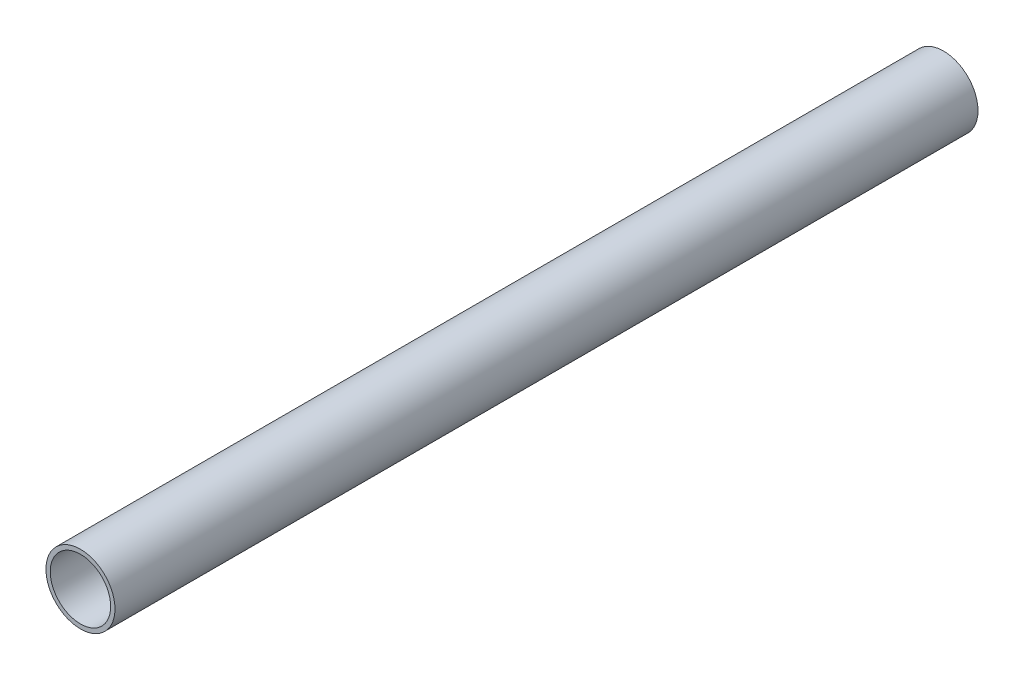
SolidWorks part; units mm, degrees
material "cf"
ref_plane "Front Plane" through (0, 0, 0) normal (0, 0, 1) x (1, 0, 0)
ref_plane "Top Plane" through (0, 0, 0) normal (0, 1, 0) x (1, 0, 0)
ref_plane "Right Plane" through (0, 0, 0) normal (1, 0, 0) x (0, 0, -1)
sketch "Sketch1" plane through (0, 0, 0) normal (0, 0, 1) x (1, 0, 0)
  circle A0 centre (0, 0) radius 8
  circle A1 centre (0, 0) radius 7
  dimension "D1" = 16
  dimension "D2" = 14
extrude "Boss-Extrude1" add sketch "Sketch1" along normal blind 200
